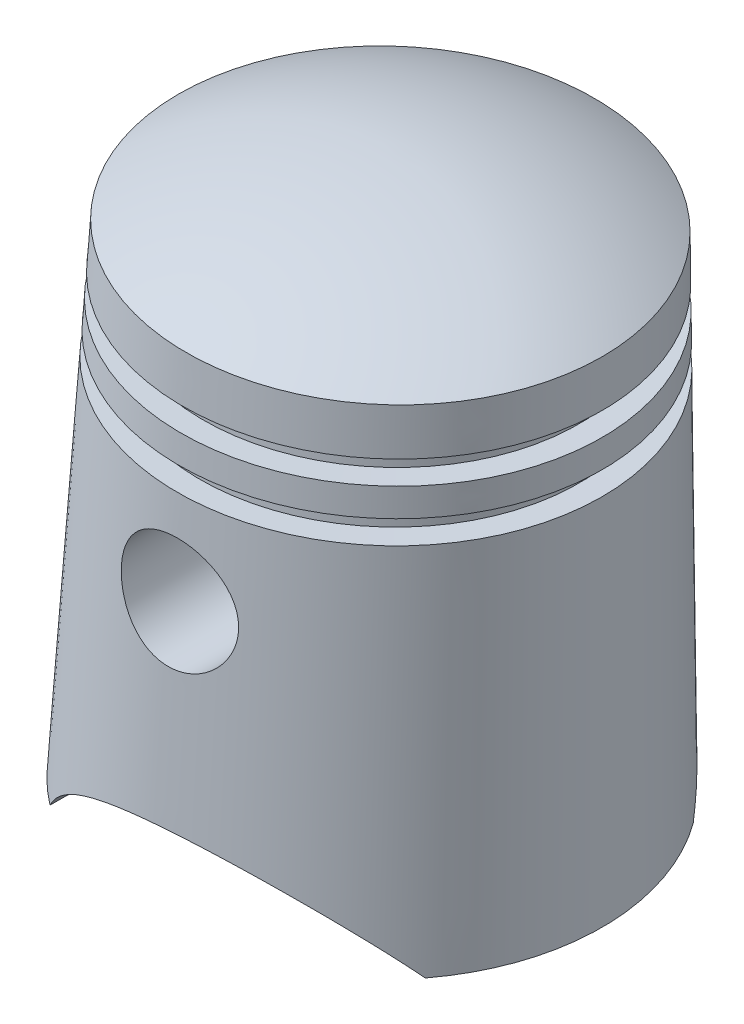
SolidWorks part; units mm, degrees
ref_plane "Płaszczyzna przednia" through (0, 0, 0) normal (0, 0, 1) x (1, 0, 0)
ref_plane "Płaszczyzna górna" through (0, 0, 0) normal (0, 1, 0) x (1, 0, 0)
ref_plane "Płaszczyzna prawa" through (0, 0, 0) normal (1, 0, 0) x (0, 0, -1)
sketch "Szkic2" plane through (0, 0, 0) normal (0, 0, 1) x (1, 0, 0)
  line L0 (0, 0) -> (22.5, 0) construction
  line L1 (0, 60) -> (0, 0) construction
  line L2 (22.5, 53) -> (22.5, 48)
  line L3 (22.5, 48) -> (20, 48)
  line L4 (20, 48) -> (20, 45.5)
  line L5 (20, 45.5) -> (22.5, 45.5)
  line L6 (22.5, 45.5) -> (22.5, 42.5)
  line L7 (22.5, 42.5) -> (20, 42.5)
  line L8 (20, 42.5) -> (20, 40)
  line L9 (20, 40) -> (22.5, 40)
  line L10 (22.5, 40) -> (22.5, 0)
  line L11 (20.5, 51.8855) -> (20.5, 50)
  line L12 (20.5, 50) -> (18, 50)
  line L13 (18, 50) -> (18, 44)
  line L14 (18, 44) -> (18, 44)
  line L15 (18, 44) -> (18, 44)
  line L16 (18, 44) -> (18, 44)
  line L17 (18, 44) -> (18, 38)
  line L18 (18, 38) -> (20.5, 38)
  line L19 (20.5, 38) -> (20.5, 0)
  line L20 (20.5, 0) -> (22.5, 0)
  line L21 (0, 60) -> (-0.0734, 58.0013)
  arc A0 (0, 60) -> (22.5, 53) centre (-1.6517, 15.0303) cw
  arc A1 (-0.0734, 58.0013) -> (20.5, 51.8855) centre (-1.6517, 15.0303) cw
  dimension "D8" = 45
  dimension "H0" = 40
  dimension "D2" = 2.5
  dimension "D3" = 2.5
  dimension "D4" = 3
  dimension "D5" = 2.5
  dimension "D6" = 5
  dimension "D9" = 22.5
  dimension "Wysokość" = 60
  dimension "D10" = 2
revolve "Obrót2" add sketch "Szkic2" angle 360 about L21
sketch "Szkic5" plane through (0, 0, 0) normal (0, 0, 1) x (1, 0, 0)
  line L0 (0, 0) -> (0, 10) construction
  line L4 (18, 0) -> (-18, 0)
  arc A1 (-18, 0) -> (18, 0) centre (0, -11.2) cw
  point P6 (0, 0)
  dimension "D1" = 10
  dimension "D2" = 36
sketch "Szkic7" plane through (0, 0, 0) normal (0, 0, 1) x (1, 0, 0)
  line L0 (0, 0) -> (0, 30.7278) construction
  line L1 (-21.4133, 41.5211) -> (20, 40) construction
  circle A0 centre (0, 30.7278) radius 6
  dimension "D1" = 12
  dimension "D2" = 10
extrude "Wytnij-wyciągnięcie1" cut sketch "Szkic7" against normal through all both and the other way through all
sketch "Szkic8" plane through (0, 0, 0) normal (0, 0, 1) x (1, 0, 0)
  circle A0 centre (0, 30.7278) radius 7.5
  circle A1 centre (0, 30.7278) radius 6 construction
  circle A2 centre (0, 30.7278) radius 6
  dimension "D1" = 15
extrude "Dodanie-wyciągnięcie2" add sketch "Szkic8" against normal up to next from offset 10 contours A0 | A2 offset against normal yes
mirror "Lustro1" about plane through (0, 0, 0) normal (0, 0, 1) of "Dodanie-wyciągnięcie2"
extrude "Wytnij-wyciągnięcie2" cut sketch "Szkic5" against normal through all both and the other way through all contours A1 L4
